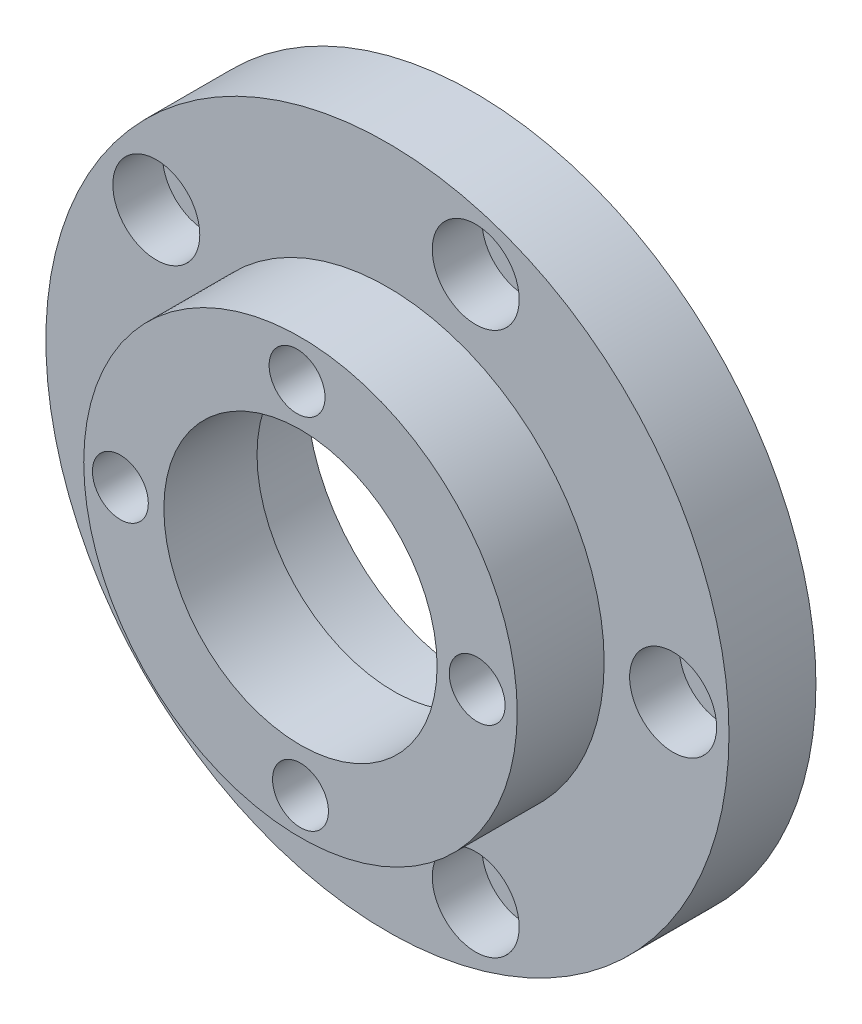
SolidWorks part; units mm, degrees
ref_plane "Front Plane" through (0, 0, 0) normal (0, 0, 1) x (1, 0, 0)
ref_plane "Top Plane" through (0, 0, 0) normal (0, 1, 0) x (1, 0, 0)
ref_plane "Right Plane" through (0, 0, 0) normal (1, 0, 0) x (0, 0, -1)
sketch "Sketch1" plane through (0, 0, 0) normal (0, 0, 1) x (1, 0, 0)
  circle A0 centre (0, 0) radius 27.5
  dimension "D1" = 55
extrude "BottomLip" add sketch "Sketch1" along normal blind 7
sketch "Sketch2" plane through (0, 0, 7) normal (0, 0, 1) x (1, 0, 0)
  circle A0 centre (0, 0) radius 11
  circle A1 centre (0, 0) radius 17.45
  dimension "D1" = 22
  dimension "D2" = 34.9
extrude "UpperRing" add sketch "Sketch2" along normal blind 7 contours A1 | A0
sketch "Sketch4" plane through (0, 0, 7) normal (0, 0, 1) x (1, 0, 0)
  circle A0 centre (0, 0) radius 11 construction
  circle A1 centre (0, 0) radius 11
extrude "MiddleHole" cut sketch "Sketch4" against normal up to surface (7 mm away) up to face at (27.5, 0, 0)
sketch "Sketch5" plane through (0, 0, 7) normal (0, 0, 1) x (1, 0, 0)
  circle A0 centre (0, 0) radius 23 construction
  circle A1 centre (23, 0) radius 2
  circle A2 centre (7.1074, -21.8743) radius 2
  circle A3 centre (-18.6074, -13.5191) radius 2
  circle A4 centre (-18.6074, 13.5191) radius 2
  circle A5 centre (7.1074, 21.8743) radius 2
  point P17 (0, 0)
  dimension "D1" = 46
  dimension "D2" = 4
  dimension "D3" = 5
extrude "StatorHoles" cut sketch "Sketch5" against normal up to surface (7 mm away) up to face at (11, 0, 0)
sketch "Sketch6" plane through (0, 0, 0) normal (0, 0, -1) x (-1, 0, 0)
  circle A0 centre (0, 0) radius 13.5
  dimension "D1" = 27
extrude "InnerBearingHole" cut sketch "Sketch6" against normal blind 6.5
sketch "Sketch7" plane through (0, 0, 14) normal (0, 0, 1) x (1, 0, 0)
  line L0 (11, 0) -> (17.45, 0) construction
  circle A0 centre (14.225, 0) radius 2.25
  circle A1 centre (0, 0) radius 11 construction
  circle A2 centre (0, 0) radius 17.45 construction
  circle A3 centre (0, -14.5) radius 2.25
  circle A4 centre (-14.5, -0.275) radius 2.25
  circle A5 centre (-0.275, 14.225) radius 2.25
  point P18 (-0.1375, -0.1375)
  dimension "D1" = 4.5
  dimension "D2" = 4
extrude "MountingHoles" cut sketch "Sketch7" against normal blind 6
sketch "Sketch8" plane through (0, 0, 7) normal (0, 0, 1) x (1, 0, 0)
  circle A0 centre (23, 0) radius 3.5
  circle A1 centre (7.1074, -21.8743) radius 3.5
  circle A2 centre (-18.6074, -13.5191) radius 3.5
  circle A3 centre (-18.6074, 13.5191) radius 3.5
  circle A4 centre (7.1074, 21.8743) radius 3.5
  dimension "D1" = 7
  dimension "D2" = 7
  dimension "D3" = 7
  dimension "D4" = 7
  dimension "D5" = 7
extrude "Cut-Extrude1" cut sketch "Sketch8" against normal blind 4
